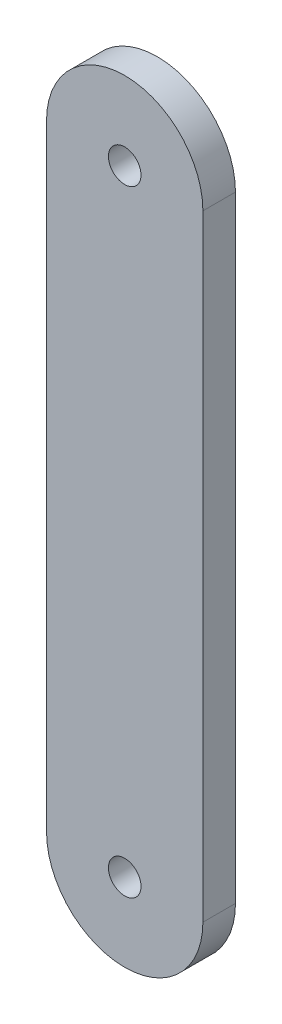
SolidWorks part; units mm, degrees
ref_plane "前视基准面" through (0, 0, 0) normal (0, 0, 1) x (1, 0, 0)
ref_plane "上视基准面" through (0, 0, 0) normal (0, 1, 0) x (1, 0, 0)
ref_plane "右视基准面" through (0, 0, 0) normal (1, 0, 0) x (0, 0, -1)
ref_plane "基准面4" through (0, 0, 5) normal (0, 0, 1) x (1, 0, 0)
sketch "草图1" plane through (0, 0, 5) normal (0, 0, 1) x (1, 0, 0)
  line L0 (12, -47.28) -> (12, 47.28)
  line L1 (-12, 47.28) -> (-12, -47.28)
  circle A0 centre (0, -47.28) radius 2.5
  circle A1 centre (0, 47.28) radius 2.5
  arc A2 (12, 47.28) -> (-12, 47.28) centre (0, 47.28) ccw
  arc A3 (-12, -47.28) -> (12, -47.28) centre (0, -47.28) ccw
  dimension "D1" = 5
  dimension "D2" = 5
extrude "凸台-拉伸1" add sketch "草图1" against normal blind 5
